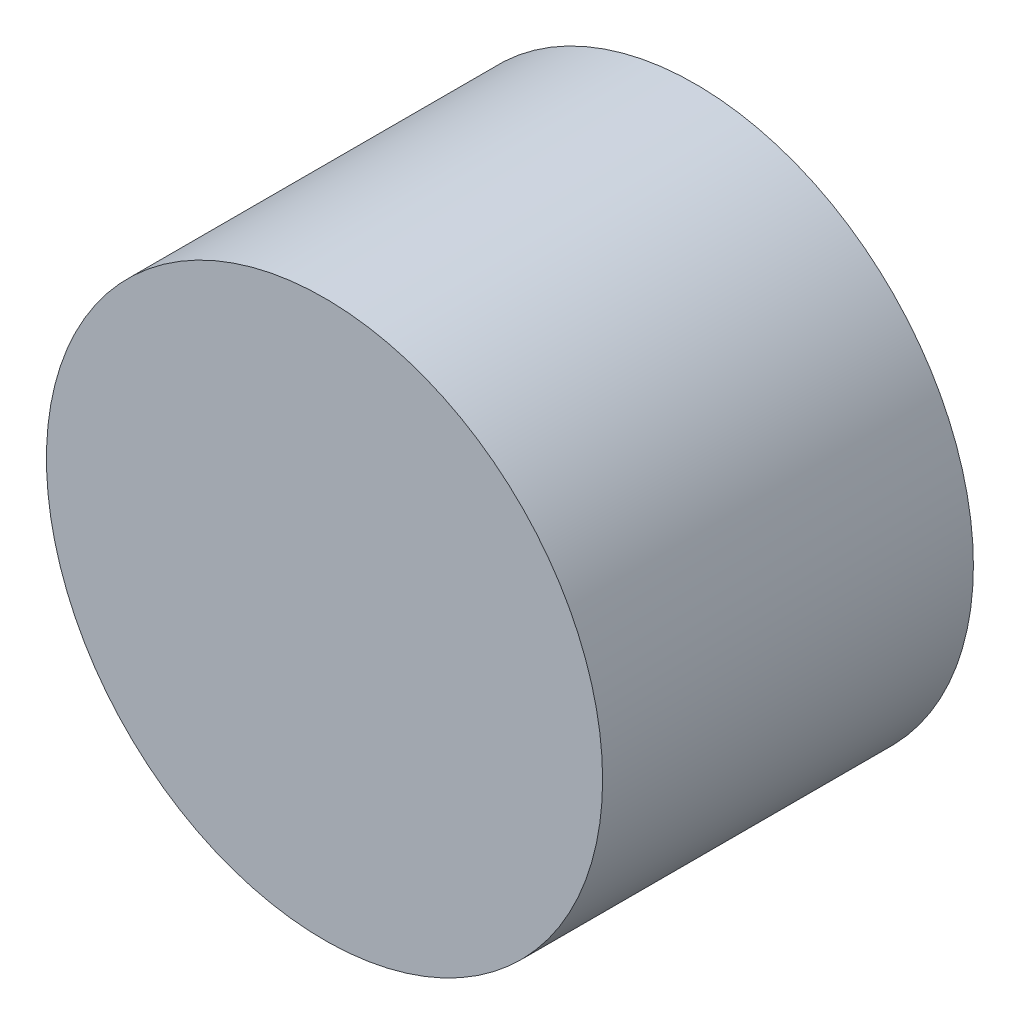
SolidWorks part; units mm, degrees
ref_plane "Plan de face" through (0, 0, 0) normal (0, 0, 1) x (1, 0, 0)
ref_plane "Plan de dessus" through (0, 0, 0) normal (0, 1, 0) x (1, 0, 0)
ref_plane "Plan de droite" through (0, 0, 0) normal (1, 0, 0) x (0, 0, -1)
sketch "Esquisse1" plane through (0, 0, 0) normal (0, 0, 1) x (1, 0, 0)
  circle A0 centre (0, 0) radius 60
  dimension "D1" = 120
extrude "Boss.-Extru.1" add sketch "Esquisse1" along normal blind 80
